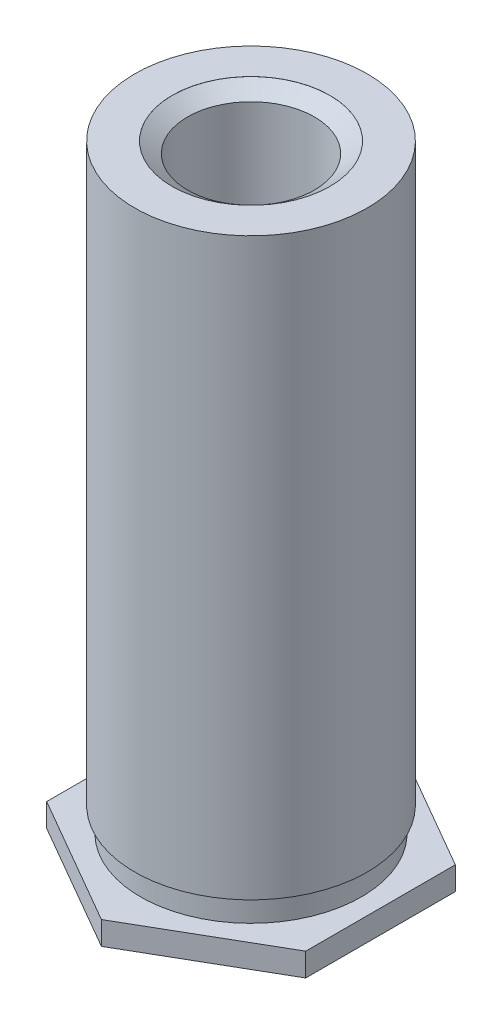
SolidWorks part; units mm, degrees
revolve "Body" add sketch "BodySke"
sketch "BodySke" plane through (0, 0, 0) normal (0, 0, 1) x (1, 0, 0)
  line L0 (3.556, 0) -> (4.5964, 0)
  line L1 (4.5964, 0) -> (4.5964, 0.7112)
  line L2 (4.5964, 0.7112) -> (3.3782, 0.7112)
  line L3 (1.9406, 19.05) -> (1.9406, 9.525)
  line L4 (3.556, 1.458) -> (3.3782, 1.458)
  line L5 (3.3782, 1.458) -> (3.3782, 0.7112)
  line L6 (3.556, 0.0025) -> (3.556, 0)
  line L7 (1.016, 18.2575) -> (3.6522, 18.2575) construction
  line L8 (3.556, 19.05) -> (1.9406, 19.05)
  line L9 (0, 0) -> (0, 15.24) construction
  line L10 (3.556, 0.0025) -> (0, 0.0025)
  line L11 (3.556, 19.05) -> (3.556, 1.458)
  line L12 (0, 9.525) -> (1.9406, 9.525)
  line L13 (0, 9.525) -> (0, 0.0025)
  line L14 (1.016, 9.525) -> (3.6522, 9.525) construction
  line L15 (1.016, 9.525) -> (3.6522, 9.525) construction
  dimension "E_dia" = 9.1928
  dimension "Thread_min" = 3.8811
  dimension "C_dia" = 7.112
  dimension "Thread_limit" = 9.525
  dimension "Advance" = 0.7925
  dimension "Thread_depth" = 9.525
  dimension "Drill_depth" = 9.525
  dimension "Length" = 19.05
  dimension "Clinching_ht" = 0.7112
  dimension "Groove_wid" = 0.7468
  dimension "Groove_dia" = 6.7564
  dimension "D1" = 0.0025
cosmetic thread "ThreadCosmetic" [suppressed]
revolve "EndChamfer" cut sketch "EndChamferSke" angle 360 about L0
sketch "EndChamferSke" plane through (0, 0, 0) normal (0, 0, 1) x (1, 0, 0)
  line L0 (0, -2.54) -> (0, 7.62) construction
  line L1 (0, 0) -> (0, 15.24) construction
  line L6 (2.413, 19.0475) -> (1.9406, 18.7168)
  line L7 (2.413, 19.0475) -> (2.413, 19.304)
  line L8 (1.9406, 18.7168) -> (1.9406, 19.304)
  line L9 (2.413, 19.304) -> (1.9406, 19.304)
  line L10 (3.556, 19.05) -> (-3.556, 19.05) construction
  dimension "D1" = 0.254
  dimension "Thread_nominal" = 4.826
  dimension "D2" = 34.99
  dimension "Thread_min" = 3.8811
  dimension "Inset" = 0.0025
revolve "TapDrill" cut sketch "TapDriSke" angle 360 about L0
sketch "TapDriSke" plane through (0, 0, 0) normal (0, 0, 1) x (1, 0, 0)
  line L0 (0, 0) -> (0, 15.24) construction
  line L1 (0, 0) -> (0, 15.24) construction
  line L2 (1.9406, 5.5626) -> (1.9406, 19.05)
  line L3 (3.556, 19.05) -> (-3.556, 19.05) construction
  line L4 (1.9406, 5.5626) -> (0, 4.7588)
  line L5 (0, 4.7588) -> (0, 19.05)
  line L6 (0, 19.05) -> (1.9406, 19.05)
  line L7 (1.9406, 9.525) -> (1.9406, 19.05) construction
  line L8 (0, 4.7588) -> (-1.9406, 5.5626) construction
  line L9 (-1.9406, 19.05) -> (-1.9406, 9.525) construction
  line L10 (0, 1.458) -> (4.826, 1.458) construction
  dimension "D1" = 135
ref_plane "Plane1" through (0, 0, 0) normal (0, 0, 1) x (1, 0, 0)
ref_plane "Plane2" through (0, 0, 0) normal (0, 1, 0) x (1, 0, 0)
ref_plane "Plane3" through (0, 0, 0) normal (1, 0, 0) x (0, 0, -1)
ref_plane "Plane4" through (0, -0.5486, 0) normal (0, 1, 0) x (-1, 0, 0)
sketch "ThdSchSke" plane through (0, 0, 0) normal (0, 0, 1) x (1, 0, 0)
  line L0 (0, -5.08) -> (0, 7.62) construction
  line L1 (0, 0) -> (0, 15.24) construction
  line L2 (0, 19.0475) -> (2.413, 19.0475) construction
  line L3 (2.413, 19.0475) -> (-2.413, 19.0475) construction
  line L4 (2.413, 19.0475) -> (1.9406, 19.3783)
  line L6 (2.413, 19.0475) -> (1.9406, 18.7167)
  line L7 (1.9406, 19.3783) -> (1.9406, 18.7167)
  dimension "Thread_min" = 3.8811
revolve "ThreadSchematic" [suppressed] cut sketch "ThdSchSke" angle 360 about L0
pattern_linear "ThdSchPat" [suppressed]
sketch "HexDieSke" plane through (0, 0.7112, 0) normal (0, 1, 0) x (-1, 0, 0)
  line L0 (0, 4.5754) -> (3.9624, 2.2877)
  line L1 (3.9624, 2.2877) -> (3.9624, -2.2877)
  line L2 (3.9624, -2.2877) -> (0, -4.5754)
  line L3 (0, -4.5754) -> (-3.9624, -2.2877)
  line L4 (-3.9624, -2.2877) -> (-3.9624, 2.2877)
  line L5 (-3.9624, 2.2877) -> (0, 4.5754)
  circle A1 centre (0, 0) radius 3.9624 construction
  circle A2 centre (0, 0) radius 4.5754 construction
  circle A3 centre (0, 0) radius 4.6091
  dimension "Width_across_flats" = 7.9248
  dimension "OD" = 9.2182
extrude "HexDie" cut sketch "HexDieSke" against normal blind 0.7112
equation "' \"Length@BodySke\" = 0.75"
equation "' \"C_dia@BodySke\" = 0.28"
equation "' \"Width_across_flats@HexDieSke\" = 0.312"
equation "' \"Thread_depth@BodySke\" = 0.375"
equation "' \"Advance@BodySke\" = 0.0312"
equation "' \"Thread_min@BodySke\" = 0.1528"
equation "' \"Thread_nominal@ThreadCosmetic\" = 0.19"
equation "\"E_dia@BodySke\" = \"Width_across_flats@HexDieSke\" * 1.16"
equation "\"Clinching_ht@BodySke\" = \"C_dia@BodySke\" * 0.1"
equation "\"Groove_dia@BodySke\" = \"C_dia@BodySke\" * 0.95"
equation "\"Groove_wid@BodySke\" = \"Clinching_ht@BodySke\" * 1.05"
equation "\"Drill_depth@BodySke\" = \"Thread_depth@BodySke\""
equation "\"Drill_limit@TapDriSke\" = \"Length@BodySke\" - \"Clinching_ht@BodySke\" - \"Groove_wid@BodySke\""
equation "\"Thread_limit@BodySke\" = ((sgn( \"Length@BodySke\" - \"Thread_depth@BodySke\" )-1)*( \"Length@BodySke\" - \"Thread_depth@BodySke\" ))/-2+ \"Thread_depth@BodySke\""
equation "\"Depth@TapDriSke\" = \"Thread_limit@BodySke\" + \"Advance@BodySke\" * 5"
equation "\"Depth@TapDriSke\" = ((sgn( \"Depth@TapDriSke\" - \"Drill_limit@TapDriSke\" )-1)*( \"Depth@TapDriSke\" - \"Drill_limit@TapDriSke\" ))/-2+ \"Drill_limit@TapDriSke\""
equation "\"Depth@HexDie\" = \"Clinching_ht@BodySke\""
equation "\"OD@HexDieSke\" =  \"Width_across_flats@HexDieSke\" * 1.16 + 0.001"
equation "\"Thread_nominal@EndChamferSke\" = \"Thread_nominal@ThreadCosmetic\""
equation "\"Thread_min@EndChamferSke\" = \"Thread_min@BodySke\""
equation "\"D2@EndChamferSke\" = \"Vee_angle@ThdSchSke\" / 2 - 0.01"
equation "\"Thread_nominal@ThdSchSke\" = \"Thread_nominal@ThreadCosmetic\""
equation "\"Thread_min@ThdSchSke\" = \"Thread_min@BodySke\""
equation "\"Num_threads@ThdSchPat\" = int(  ( \"Thread_limit@BodySke\" - \"Inset@EndChamferSke\" ) / \"Advance@BodySke\" + 0.999 )  + 1"
equation "\"Advance@ThdSchPat\" = (  \"Thread_limit@BodySke\" - \"Inset@EndChamferSke\" ) /  (\"Num_threads@ThdSchPat\" - 1) 'relax it"
